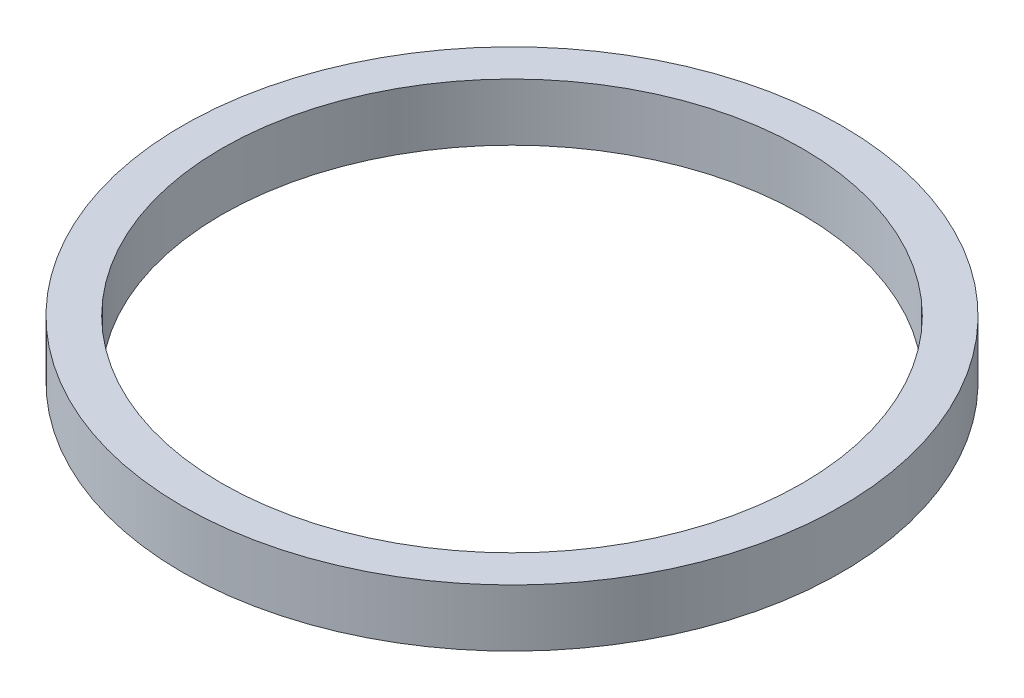
SolidWorks part; units mm, degrees
material "Silicon Rubber"
ref_plane "Front Plane" through (0, 0, 0) normal (0, 0, 1) x (1, 0, 0)
ref_plane "Top Plane" through (0, 0, 0) normal (0, 1, 0) x (1, 0, 0)
ref_plane "Right Plane" through (0, 0, 0) normal (1, 0, 0) x (0, 0, -1)
sketch "Sketch1" plane through (0, 0, 0) normal (0, 1, 0) x (1, 0, 0)
  circle A0 centre (0, 0) radius 23
  circle A1 centre (0, 0) radius 20.25
  dimension "D1" = 46
  dimension "D2" = 46
  dimension "D3" = 40.5
extrude "Boss-Extrude1" add sketch "Sketch1" along normal blind 4
